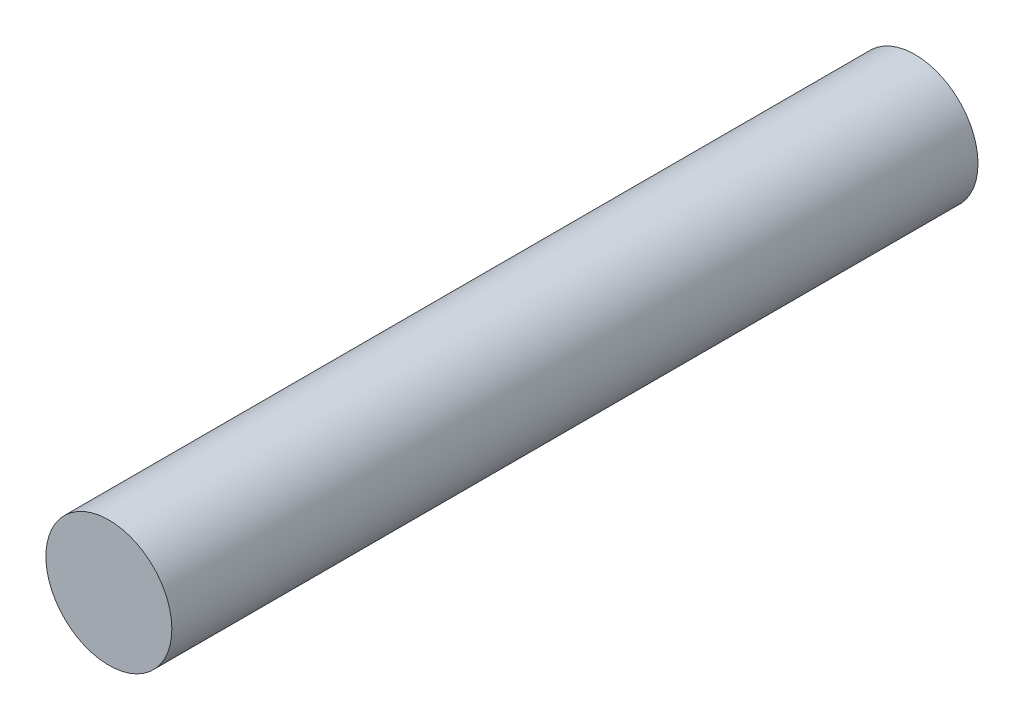
SolidWorks part; units mm, degrees
ref_plane "Front" through (0, 0, 0) normal (0, 0, 1) x (1, 0, 0)
ref_plane "Top" through (0, 0, 0) normal (0, 1, 0) x (1, 0, 0)
ref_plane "Right" through (0, 0, 0) normal (1, 0, 0) x (0, 0, -1)
sketch "Esquisse1" plane through (0, 0, 0) normal (0, 0, 1) x (1, 0, 0)
  circle A0 centre (0, 0) radius 2.5
  dimension "D1" = 5
extrude "Boss.-Extru.1" add sketch "Esquisse1" along normal mid plane 32
